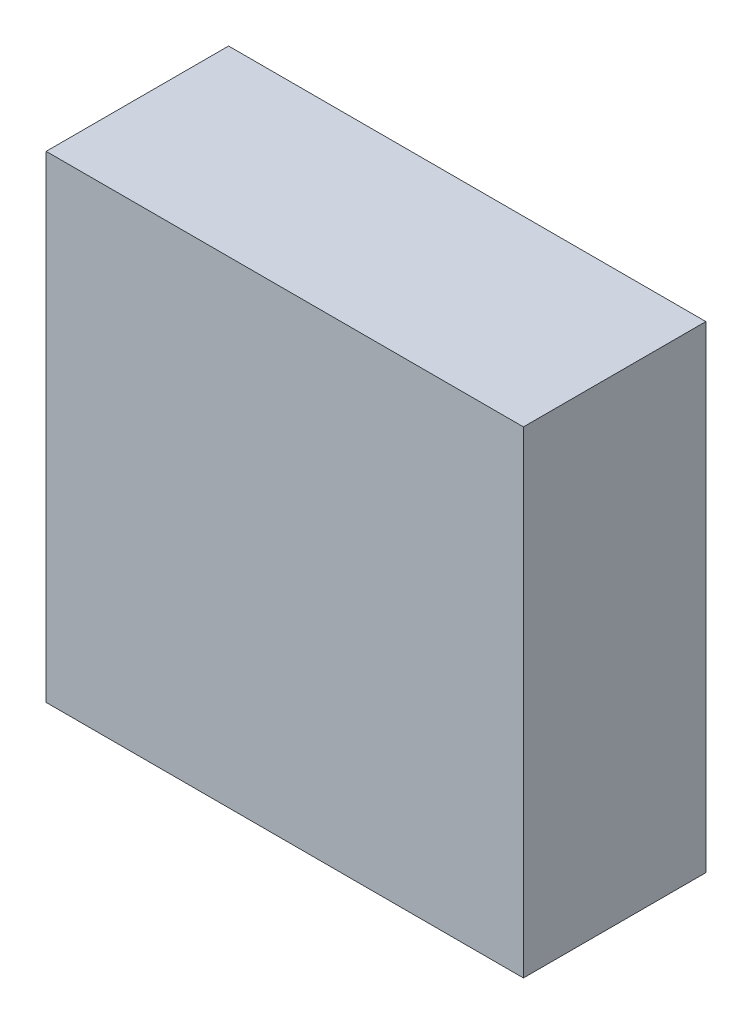
SolidWorks part; units mm, degrees
ref_plane "Ebene vorne" through (0, 0, 0) normal (0, 0, 1) x (1, 0, 0)
ref_plane "Ebene oben" through (0, 0, 0) normal (0, 1, 0) x (1, 0, 0)
ref_plane "Ebene rechts" through (0, 0, 0) normal (1, 0, 0) x (0, 0, -1)
sketch "Skizze1" plane through (0, 0, 0) normal (0, 0, 1) x (1, 0, 0)
  line L0 (-1.27, 1.3462) -> (1.3462, 1.3462)
  line L1 (1.3462, 1.3462) -> (1.3462, -1.27)
  line L2 (1.3462, -1.27) -> (-1.27, -1.27)
  line L3 (-1.27, -1.27) -> (-1.27, 1.3462)
extrude "Component_Outline" add sketch "Skizze1" along normal blind 1 separate body
sketch3d "3D-Skizze1"
  line L0 (0, 0, 0) -> (1, 0, 0)
  line L1 (0, 0, 0) -> (0, 1, 0)
  line L2 (0, 0, 0) -> (0, 0, 1)
  point P0 (0, 0, 0)
